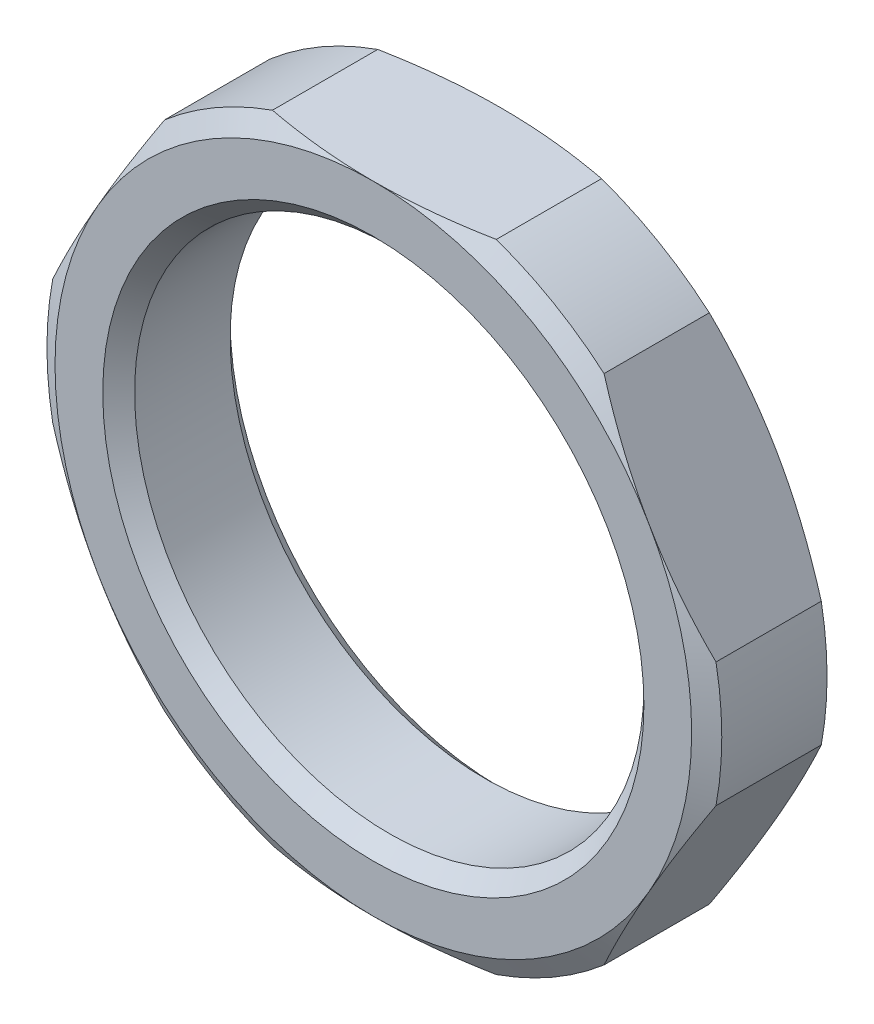
SolidWorks part; units mm, degrees
ref_plane "Front" through (0, 0, 0) normal (0, 0, 1) x (1, 0, 0)
ref_plane "Top" through (0, 0, 0) normal (0, 1, 0) x (1, 0, 0)
ref_plane "Right" through (0, 0, 0) normal (1, 0, 0) x (0, 0, -1)
sketch "Hex_Sketch" plane through (0, 0, 0) normal (0, 0, 1) x (1, 0, 0)
  line L1 (2.8868, 5) -> (-2.8868, 5)
  line L2 (-2.8868, 5) -> (-5.7735, 0)
  line L3 (-5.7735, 0) -> (-2.8868, -5)
  line L4 (-2.8868, -5) -> (2.8868, -5)
  line L5 (2.8868, -5) -> (5.7735, 0)
  line L6 (5.7735, 0) -> (2.8868, 5)
  circle A0 centre (0, 0) radius 5 construction
  circle A1 centre (0, 0) radius 4
  point P10 (-5, 0)
  dimension "ID" = 8
  dimension "Flats" = 10
extrude "Hex" add sketch "Hex_Sketch" along normal mid plane 2
sketch "Hex Cham OD_Sketch" plane through (0, 0, 0) normal (0, 1, 0) x (1, 0, 0)
  line L0 (-5.7735, 1) -> (-5.7735, 0.5534)
  line L1 (-5.7735, -1) -> (-5.7735, 1) construction
  line L2 (-5.7735, 0.5534) -> (-5, 1)
  line L3 (-2.8868, 1) -> (-5.7735, 1) construction
  line L4 (-5, 1) -> (-5.7735, 1)
  line L5 (-5.7735, 0) -> (-7.0458, 0) construction
  line L6 (-5, -1) -> (-5.7735, -1)
  line L7 (-5.7735, -0.5534) -> (-5, -1)
  line L8 (-5.7735, -1) -> (-5.7735, -0.5534)
  line L9 (0, 5.3047) -> (0, -4.6149) construction
  line L10 (0, -1) -> (0, 1) construction
  dimension "Angle" = 30
revolve "Hex Cham OD" cut sketch "Hex Cham OD_Sketch" angle 360 about L9
chamfer "Hex Cham ID" distance 0.25 2 edges at (4, 0, -1) (4, 0, 1)
sketch "Hex Round_Sketch" plane through (0, 0, 0) normal (0, 0, 1) x (1, 0, 0)
  circle A0 centre (0, 0) radius 5.3
  dimension "Dia" = 10.6
extrude "Hex Round" cut sketch "Hex Round_Sketch" against normal through all and the other way through all flip side to cut
